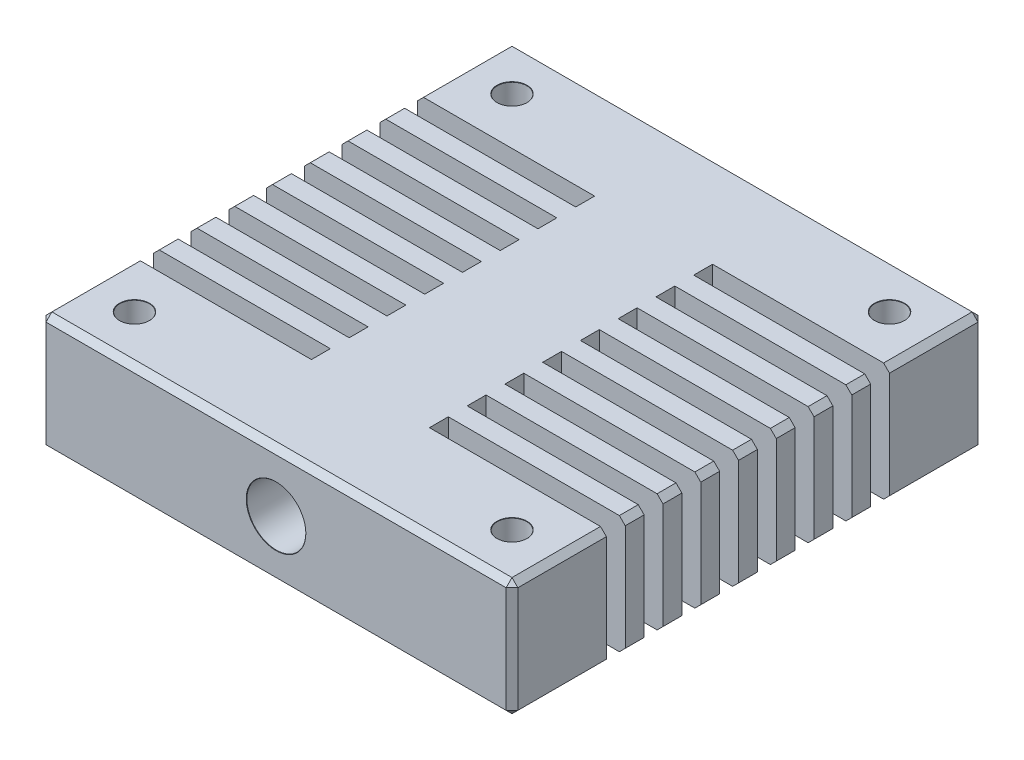
SolidWorks part; units mm, degrees
ref_plane "Plan de face" through (0, 0, 0) normal (0, 0, 1) x (1, 0, 0)
ref_plane "Plan de dessus" through (0, 0, 0) normal (0, 1, 0) x (1, 0, 0)
ref_plane "Plan de droite" through (0, 0, 0) normal (1, 0, 0) x (0, 0, -1)
sketch "Esquisse1" plane through (0, 0, 0) normal (0, 1, 0) x (1, 0, 0)
  line L1 (0, 0) -> (40, 0)
  line L2 (0, 0) -> (0, 40)
  line L3 (0, 40) -> (40, 40)
  line L4 (40, 0) -> (40, 40)
  dimension "D1" = 40
  dimension "D2" = 40
extrude "Boss.-Extru.1" add sketch "Esquisse1" along normal blind 10
sketch "Esquisse4" plane through (0, 0, 0) normal (0, 0, 1) x (1, 0, 0)
  line L0 (0, 10) -> (40, 10) construction
  line L1 (40, 10) -> (40, 0) construction
  circle A0 centre (20, 5) radius 2
  dimension "D1" = 4
  dimension "D2" = 5
  dimension "D3" = 20
hole_wizard "Diamètre du perçage Ø4.0 (4)1" positions "Esquisse6" profile "Esquisse5" hole size "Ø4.0" standard "ISO" end condition through all
sketch "Esquisse6" plane through (0, 0, 0) normal (0, 0, 1) x (1, 0, 0)
  point P0 (20, 5)
sketch "Esquisse5" plane through (20, 5, 0) normal (1, 0, 0) x (0, -1, 0)
  line L0 (0, 0) -> (0, 40)
  line L1 (0, 40) -> (2, 40)
  line L2 (2, 40) -> (2, 0)
  line L5 (2, 0) -> (0, 0)
  line L11 (0, -6.35) -> (0, 107.95) construction
  dimension "Diamètre du perçage jusqu'au prochain" = 4
  dimension "Profondeur du perçage jusqu'au prochain" = 40
sketch "Esquisse2" plane through (0, 0, 0) normal (0, 0, 1) x (1, 0, 0)
  line L0 (40, 10) -> (40, 0) construction
  line L1 (0, 10) -> (40, 10) construction
  circle A0 centre (20, 5) radius 3
  dimension "D1" = 6
  dimension "D2" = 20
  dimension "D3" = 5
hole_wizard "Trou pour taraudage pour trou taraudé M61" positions "Esquisse8" profile "Esquisse9" hole size "M6" standard "ISO"
sketch "Esquisse8" plane through (0, 0, 0) normal (0, 0, 1) x (1, 0, 0)
  point P0 (20, 5)
sketch "Esquisse9" plane through (20, 5, 0) normal (1, 0, 0) x (0, -1, 0)
  line L0 (0, 0) -> (0, 9.5022)
  line L1 (0, 9.5022) -> (2.5, 8)
  line L2 (2.5, 8) -> (2.5, 0.025)
  line L3 (2.5, 0.025) -> (2.525, 0)
  line L5 (2.525, 0) -> (0, 0)
  line L6 (-2.5, 0.025) -> (-2.525, 0) construction
  line L10 (0, 9.5022) -> (-2.5, 8) construction
  line L11 (0, -6.35) -> (0, 107.95) construction
  dimension "Diamètre du perçage" = 5
  dimension "Profondeur du perçage" = 8
  dimension "Diamètre du fraisage entrant" = 5.05
  dimension "Angle du fraisage entrant" = 90
  dimension "Angle de pointe" = 118
sketch "Esquisse3" plane through (0, 0, -40) normal (0, 0, -1) x (-1, 0, 0)
  line L0 (-40, 10) -> (-40, 0) construction
  line L1 (-40, 10) -> (0, 10) construction
  circle A0 centre (-20, 5) radius 3
  dimension "D1" = 6
  dimension "D2" = 20
  dimension "D3" = 5
hole_wizard "Diamètre du perçage Ø6.0 (6)1" positions "Esquisse11" profile "Esquisse12" hole size "Ø6.0" standard "ISO"
sketch "Esquisse11" plane through (0, 0, -40) normal (0, 0, -1) x (-1, 0, 0)
  point P0 (-20, 5)
sketch "Esquisse12" plane through (20, 5, -40) normal (1, 0, 0) x (0, 1, 0)
  line L0 (0, 0) -> (0, 21.8026)
  line L1 (0, 21.8026) -> (3, 20)
  line L2 (3, 20) -> (3, 0)
  line L5 (3, 0) -> (0, 0)
  line L10 (0, 21.8026) -> (-3, 20) construction
  line L11 (0, -6.35) -> (0, 107.95) construction
  dimension "Diamètre du perçage" = 6
  dimension "Profondeur du perçage" = 20
  dimension "Angle de pointe" = 118
sketch "Esquisse16" plane through (0, 0, 0) normal (0, -1, 0) x (1, 0, 0)
  line L0 (0, 0) -> (40, 0) construction
  line L1 (0, -40) -> (0, 0) construction
  line L2 (40, 0) -> (40, -40) construction
  line L3 (40, -40) -> (0, -40) construction
  circle A0 centre (4, -4) radius 1.5
  circle A1 centre (36, -4) radius 1.5
  circle A2 centre (36, -36) radius 1.5
  circle A3 centre (4, -36) radius 1.5
  circle A4 centre (20, -36) radius 1.5
  dimension "D3" = 3
  dimension "D6" = 3
  dimension "D7" = 3
  dimension "D10" = 3
  dimension "D11" = 20
  dimension "D15" = 3
  dimension "D1" = 4
  dimension "D2" = 4
  dimension "D4" = 4
  dimension "D5" = 4
  dimension "D8" = 4
  dimension "D9" = 4
  dimension "D12" = 4
  dimension "D13" = 4
  dimension "D14" = 4
hole_wizard "Trou pour taraudage pour trou taraudé M31" positions "Esquisse18" profile "Esquisse17" hole size "M3" standard "ISO" end condition through all
sketch "Esquisse18" plane through (0, 0, 0) normal (0, -1, 0) x (-1, 0, 0)
  point P0 (-4, 4)
  point P3 (-36, 4)
  point P6 (-36, 36)
  point P9 (-4, 36)
sketch "Esquisse17" plane through (4, 0, -4) normal (1, 0, 0) x (0, 0, -1)
  line L0 (0, 0) -> (0, 10)
  line L1 (0, 10) -> (1.275, 10)
  line L2 (1.25, 9.975) -> (1.25, 0.025)
  line L3 (1.25, 0.025) -> (1.275, 0)
  line L5 (1.275, 0) -> (0, 0)
  line L6 (-1.25, 0.025) -> (-1.275, 0) construction
  line L7 (1.275, 10) -> (1.25, 9.975)
  line L8 (-1.275, 10) -> (-1.25, 9.975) construction
  line L11 (0, -6.35) -> (0, 107.95) construction
  dimension "Diamètre du perçage jusqu'au prochain" = 2.5
  dimension "Profondeur du perçage jusqu'au prochain" = 10
  dimension "Diamètre du fraisage entrant" = 2.55
  dimension "Angle du fraisage entrant" = 90
  dimension "Diamètre du fraisage débouchant" = 2.55
  dimension "Angle du fraisage débouchant" = 90
hole_wizard "Trou pour taraudage pour trou taraudé M32" positions "Esquisse20" profile "Esquisse19" hole size "M3" standard "ISO"
sketch "Esquisse20" plane through (0, 0, 0) normal (0, -1, 0) x (-1, 0, 0)
  point P0 (-20, 36)
sketch "Esquisse19" plane through (20, 0, -36) normal (1, 0, 0) x (0, 0, -1)
  line L0 (0, 0) -> (0, 5.7511)
  line L1 (0, 5.7511) -> (1.25, 5)
  line L2 (1.25, 5) -> (1.25, 0.025)
  line L3 (1.25, 0.025) -> (1.275, 0)
  line L5 (1.275, 0) -> (0, 0)
  line L6 (-1.25, 0.025) -> (-1.275, 0) construction
  line L10 (0, 5.7511) -> (-1.25, 5) construction
  line L11 (0, -6.35) -> (0, 107.95) construction
  dimension "Diamètre du perçage" = 2.5
  dimension "Profondeur du perçage" = 5
  dimension "Diamètre du fraisage entrant" = 2.55
  dimension "Angle du fraisage entrant" = 90
  dimension "Angle de pointe" = 118
sketch "Esquisse21" plane through (0, 0, 0) normal (0, -1, 0) x (1, 0, 0)
  line L0 (0, -40) -> (0, 0) construction
  line L1 (0, -8) -> (15, -8)
  line L2 (0, -8) -> (0, -9.6)
  line L3 (0, -9.6) -> (15, -9.6)
  line L4 (15, -8) -> (15, -9.6)
  line L5 (0, 0) -> (40, 0) construction
  line L6 (40, 0) -> (40, -40) construction
  line L7 (40, -8) -> (25, -8)
  line L8 (40, -8) -> (40, -9.6)
  line L9 (40, -9.6) -> (25, -9.6)
  line L10 (25, -8) -> (25, -9.6)
  dimension "D1" = 1.6
  dimension "D2" = 15
  dimension "D3" = 8
  dimension "D4" = 1.6
  dimension "D5" = 8
  dimension "D6" = 15
extrude "Enlèv. mat.-Extru.1" cut sketch "Esquisse21" against normal through all
pattern_linear "Répétition linéaire1" count 8 spacing 3.2 along (0, 0, -1) of "Enlèv. mat.-Extru.1"
chamfer "Chanfrein1" distance 0.5 angle 45 44 edges at (0, 10, -29.6) (0, 10, -26.4) (0, 10, -23.2) (0, 10, -20) (0, 10, -16.8) (0, 10, -13.6) (0, 10, -10.4) (40, 10, -29.6) (40, 10, -26.4) (40, 10, -23.2) (40, 10, -20) (40, 10, -16.8) (40, 10, -13.6) (40, 10, -10.4) (20, 10, -40) (0, 10, -36) (40, 10, -36) (0, 5, -40) (40, 5, -40) (0, 0, -36) (20, 0, -40) (40, 0, -36) (40, 0, -29.6) (40, 0, -26.4) (0, 0, -29.6) (0, 0, -26.4) (0, 0, -23.2) (40, 0, -23.2) (40, 0, -20) (0, 0, -20) (0, 0, -16.8) (40, 0, -16.8) (40, 0, -13.6) (0, 0, -13.6) (0, 0, -10.4) (40, 0, -10.4) (40, 10, -4) (0, 10, -4) (20, 10, 0) (0, 5, 0) (40, 5, 0) (40, 0, -4) (20, 0, 0) (0, 0, -4)
